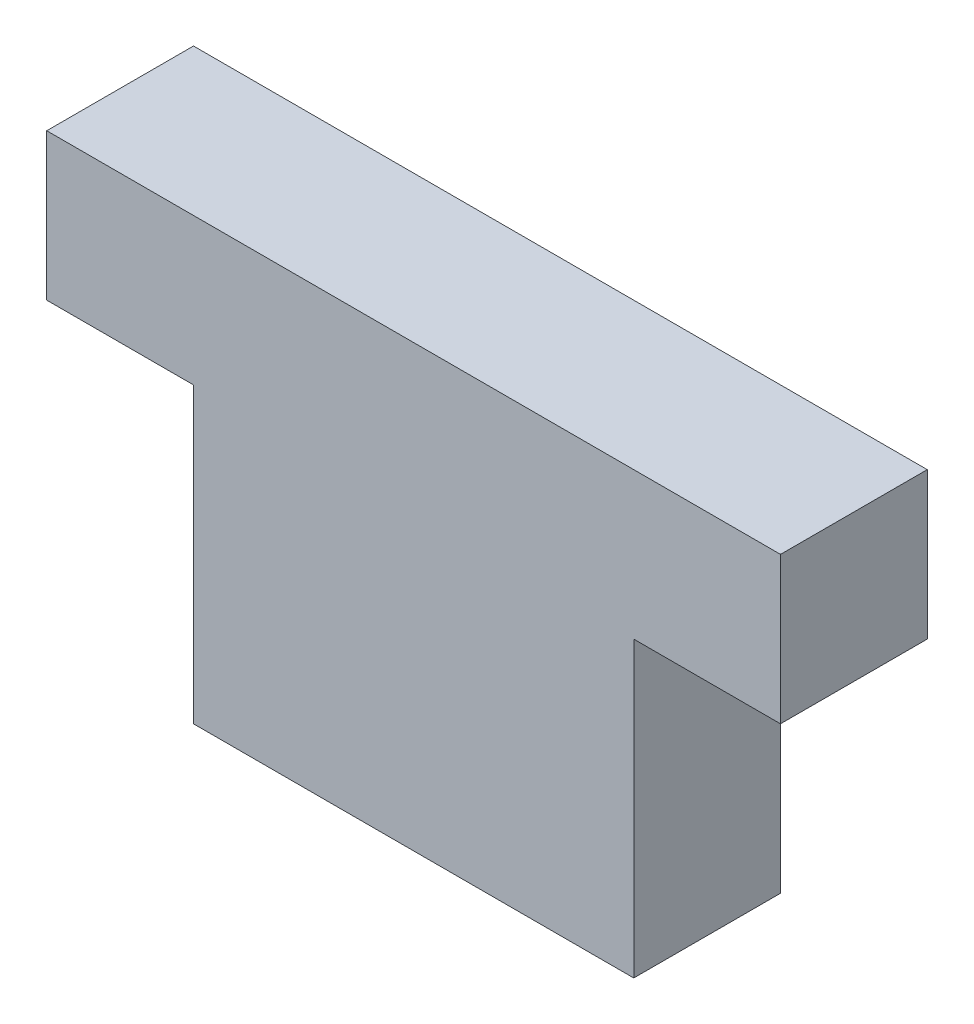
SolidWorks part; units mm, degrees
ref_plane "Front Plane" through (0, 0, 0) normal (0, 0, 1) x (1, 0, 0)
ref_plane "Top Plane" through (0, 0, 0) normal (0, 1, 0) x (1, 0, 0)
ref_plane "Right Plane" through (0, 0, 0) normal (1, 0, 0) x (0, 0, -1)
sketch "Sketch1" plane through (0, 0, 0) normal (0, 0, 1) x (1, 0, 0)
  line L0 (0, 10) -> (5, 10)
  line L2 (-15, 10) -> (-15, 0)
  line L3 (-15, 0) -> (0, 0)
  line L4 (0, 10) -> (0, 0)
  line L5 (-20, 10) -> (-15, 10)
  line L6 (-20, 10) -> (-20, 15)
  line L7 (-20, 15) -> (5, 15)
  line L8 (5, 10) -> (5, 15)
  dimension "D1" = 10
  dimension "D2" = 15
  dimension "D3" = 25
  dimension "D4" = 5
  dimension "D5" = 5
extrude "Boss-Extrude1" add sketch "Sketch1" along normal blind 5
